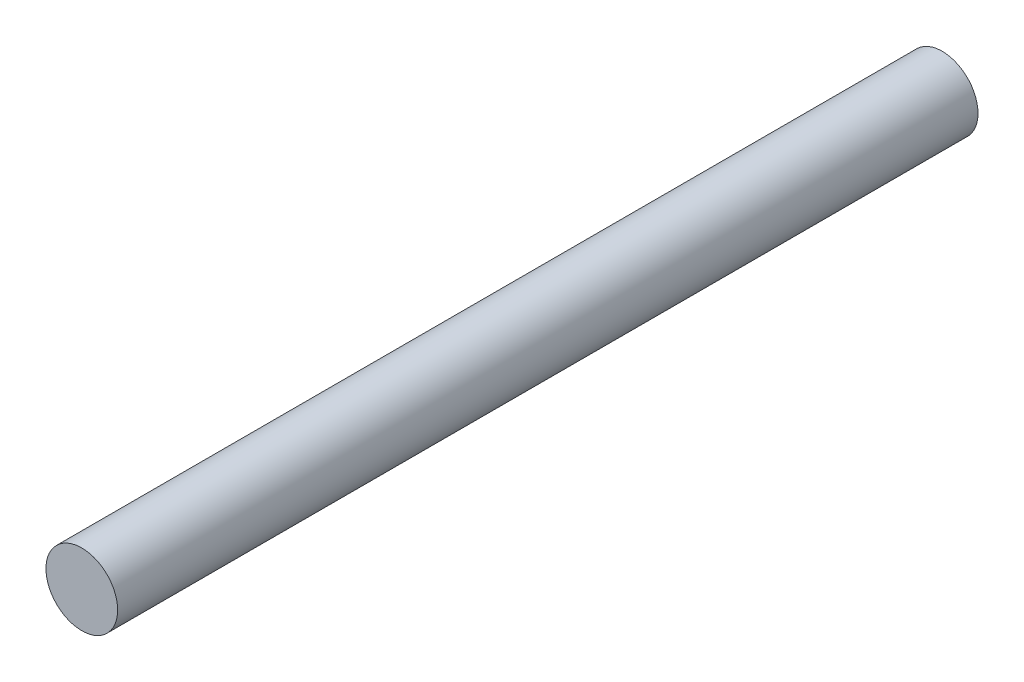
SolidWorks part; units mm, degrees
ref_plane "前视基准面" through (0, 0, 0) normal (0, 0, 1) x (1, 0, 0)
ref_plane "上视基准面" through (0, 0, 0) normal (0, 1, 0) x (1, 0, 0)
ref_plane "右视基准面" through (0, 0, 0) normal (1, 0, 0) x (0, 0, -1)
sketch "草图1" plane through (0, 0, 0) normal (0, 0, 1) x (1, 0, 0)
  circle A0 centre (0, 0) radius 2.5
  dimension "D1" = 5
extrude "凸台-拉伸1" add sketch "草图1" along normal blind 60
